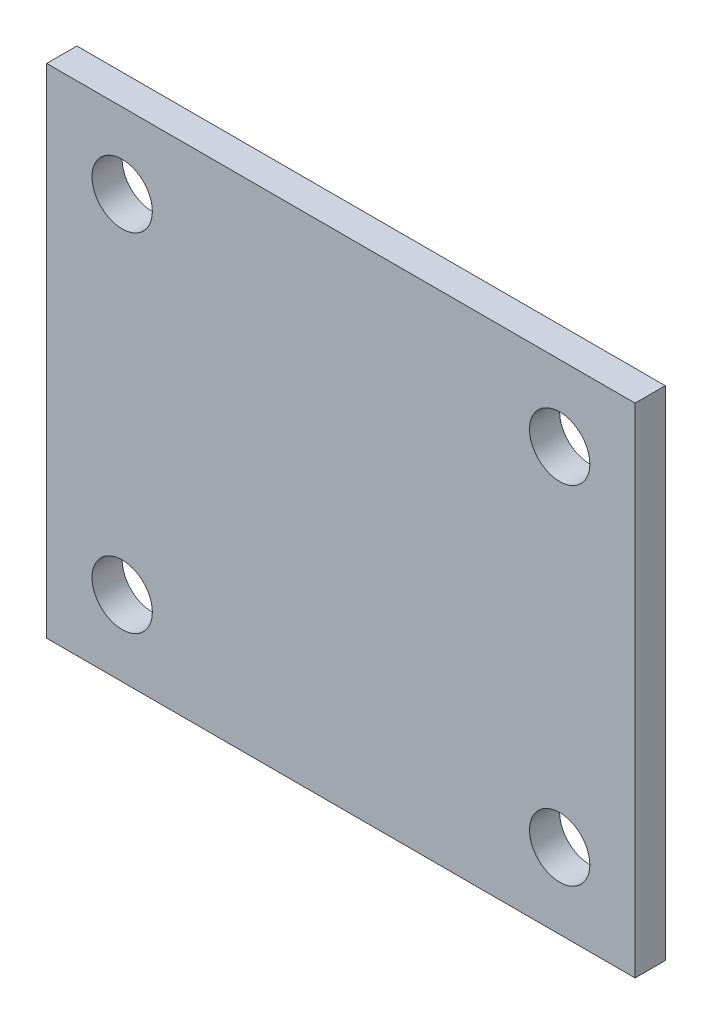
SolidWorks part; units mm, degrees
ref_plane "前基準面" through (0, 0, 0) normal (0, 0, 1) x (1, 0, 0)
ref_plane "上基準面" through (0, 0, 0) normal (0, 1, 0) x (1, 0, 0)
ref_plane "右基準面" through (0, 0, 0) normal (1, 0, 0) x (0, 0, -1)
sketch "草圖1" plane through (0, 0, 0) normal (0, 0, 1) x (1, 0, 0)
  line L1 (-14.5, 11.5) -> (14.5, 11.5) construction
  line L2 (-14.5, 11.5) -> (-14.5, -11.5) construction
  line L3 (-14.5, -11.5) -> (14.5, -11.5) construction
  line L4 (14.5, 11.5) -> (14.5, -11.5) construction
  line L5 (-14.5, 11.5) -> (14.5, -11.5) construction
  line L6 (-14.5, -11.5) -> (14.5, 11.5) construction
  line L7 (-19.5, 16.5) -> (19.5, 16.5)
  line L8 (-19.5, 16.5) -> (-19.5, -16.5)
  line L9 (-19.5, -16.5) -> (19.5, -16.5)
  line L10 (19.5, 16.5) -> (19.5, -16.5)
  line L11 (-19.5, 16.5) -> (19.5, -16.5) construction
  line L12 (-19.5, -16.5) -> (19.5, 16.5) construction
  circle A0 centre (-14.5, 11.5) radius 2
  circle A1 centre (-14.5, -11.5) radius 2
  circle A2 centre (14.5, -11.5) radius 2
  circle A3 centre (14.5, 11.5) radius 2
  point P0 (0, 0)
  point P10 (0, 0)
  dimension "D3" = 4
  dimension "D4" = 4
  dimension "D5" = 4
  dimension "D6" = 4
  dimension "D1" = 23
  dimension "D2" = 29
  dimension "D7" = 5
  dimension "D8" = 5
extrude "填料-伸長1" add sketch "草圖1" along normal blind 2
